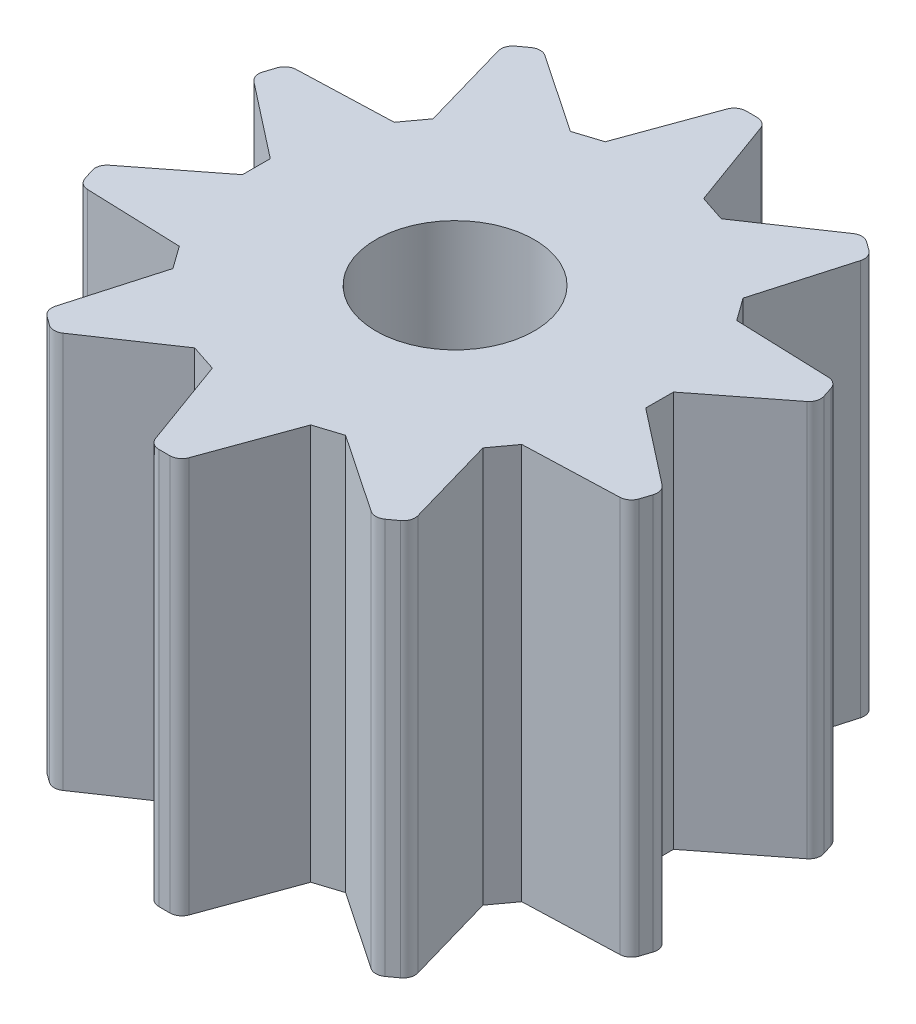
SolidWorks part; units mm, degrees
ref_plane "Front Plane" through (0, 0, 0) normal (0, 0, 1) x (1, 0, 0)
ref_plane "Top Plane" through (0, 0, 0) normal (0, 1, 0) x (1, 0, 0)
ref_plane "Right Plane" through (0, 0, 0) normal (1, 0, 0) x (0, 0, -1)
sketch "Sketch2" plane through (0, 0, 0) normal (0, 1, 0) x (1, 0, 0)
  line L0 (0, 0) -> (0, 7.4859) construction
  line L1 (-0.35, 7.4859) -> (0.35, 7.4859)
  line L2 (0.35, 7.4859) -> (1.2421, 5.0349)
  line L3 (-0.35, 7.4859) -> (-1.2421, 5.0349)
  line L4 (4.0691, 6.274) -> (1.9068, 4.8154)
  line L5 (4.0691, 6.274) -> (4.6354, 5.8625)
  line L6 (4.6354, 5.8625) -> (3.9165, 3.3553)
  line L7 (6.9319, 2.696) -> (4.3252, 2.787)
  line L8 (6.9319, 2.696) -> (7.1482, 2.0303)
  line L9 (7.1482, 2.0303) -> (5.0929, 0.4245)
  line L10 (7.1449, -1.8813) -> (5.0895, -0.2755)
  line L11 (7.1449, -1.8813) -> (6.9286, -2.547)
  line L12 (6.9286, -2.547) -> (4.3219, -2.6381)
  line L13 (4.6267, -5.7096) -> (3.9078, -3.2024)
  line L14 (4.6267, -5.7096) -> (4.0604, -6.1211)
  line L15 (4.0604, -6.1211) -> (1.8981, -4.6626)
  line L16 (0.3392, -7.3266) -> (1.2313, -4.8757)
  line L17 (0.3392, -7.3266) -> (-0.3608, -7.3266)
  line L18 (-0.3608, -7.3266) -> (-1.2528, -4.8757)
  line L19 (-4.0799, -6.1147) -> (-1.9175, -4.6562)
  line L20 (-4.0799, -6.1147) -> (-4.6462, -5.7033)
  line L21 (-4.6462, -5.7033) -> (-3.9273, -3.1961)
  line L22 (-6.9427, -2.5368) -> (-4.336, -2.6278)
  line L23 (-6.9427, -2.5368) -> (-7.159, -1.8711)
  line L24 (-7.159, -1.8711) -> (-5.1036, -0.2653)
  line L25 (-7.1556, 2.0405) -> (-5.1003, 0.4347)
  line L26 (-7.1556, 2.0405) -> (-6.9393, 2.7063)
  line L27 (-6.9393, 2.7063) -> (-4.3327, 2.7973)
  line L28 (-4.6375, 5.8688) -> (-3.9185, 3.3616)
  line L29 (-4.6375, 5.8688) -> (-4.0712, 6.2803)
  line L30 (-4.0712, 6.2803) -> (-1.9088, 4.8218)
  line L31 (-1.2421, 5.0349) -> (-1.9088, 4.8218)
  line L32 (-3.9185, 3.3616) -> (-4.3327, 2.7973)
  line L33 (-5.1003, 0.4347) -> (-5.1036, -0.2653)
  line L34 (-4.336, -2.6278) -> (-3.9273, -3.1961)
  line L35 (-1.9175, -4.6562) -> (-1.2528, -4.8757)
  line L36 (1.2313, -4.8757) -> (1.8981, -4.6626)
  line L37 (3.9078, -3.2024) -> (4.3219, -2.6381)
  line L38 (5.0895, -0.2755) -> (5.0929, 0.4245)
  line L39 (4.3252, 2.787) -> (3.9165, 3.3553)
  line L40 (1.9068, 4.8154) -> (1.2421, 5.0349)
  circle A0 centre (0, 0) radius 7.4859 construction
  circle A2 centre (0, 0) radius 6.3359 construction
  circle A3 centre (0, 0) radius 5.1859 construction
  circle A4 centre (0, 0) radius 2
  point P50 (-0.0054, 0.0796)
  dimension "D1" = 14.9717
  dimension "D2" = 1.15
  dimension "D7" = 4
  dimension "D4" = 0.35
  dimension "D5" = 110
  dimension "D3" = 1.15
  dimension "D6" = 10
extrude "Boss-Extrude1" add sketch "Sketch2" along normal blind 10
fillet "Fillet1" radius 0.3 20 edges at (-4.6375, 5, -5.8688) (-4.0712, 5, -6.2803) (-0.35, 5, -7.4859) (0.35, 5, -7.4859) (4.0691, 5, -6.274) (4.6354, 5, -5.8625) (6.9319, 5, -2.696) (7.1482, 5, -2.0303) (7.1449, 5, 1.8813) (6.9286, 5, 2.547) (4.6267, 5, 5.7096) (4.0604, 5, 6.1211) (0.3392, 5, 7.3266) (-0.3608, 5, 7.3266) (-4.0799, 5, 6.1147) (-4.6462, 5, 5.7033) (-6.9427, 5, 2.5368) (-7.159, 5, 1.8711) (-6.9393, 5, -2.7063) (-7.1556, 5, -2.0405)
